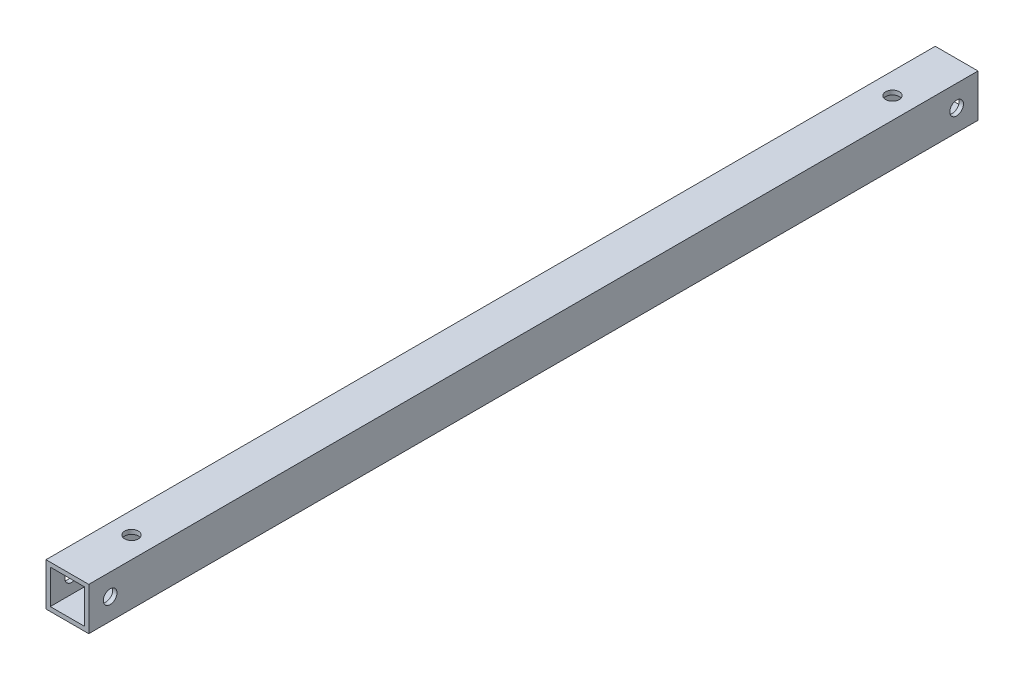
SolidWorks part; units mm, degrees
ref_plane "正面" through (0, 0, 0) normal (0, 0, 1) x (1, 0, 0)
ref_plane "平面" through (0, 0, 0) normal (0, 1, 0) x (1, 0, 0)
ref_plane "右側面" through (0, 0, 0) normal (1, 0, 0) x (0, 0, -1)
sketch "ｽｹｯﾁ1" plane through (0, 0, 0) normal (0, 0, 1) x (1, 0, 0)
  line L0 (-4, 4) -> (-4, -4)
  line L1 (-5, 5) -> (5, 5)
  line L2 (-5, 5) -> (-5, -5)
  line L3 (-5, -5) -> (5, -5)
  line L4 (5, 5) -> (5, -5)
  line L5 (-5, 5) -> (5, -5) construction
  line L6 (-5, -5) -> (5, 5) construction
  line L7 (-4, -4) -> (4, -4)
  line L8 (4, 4) -> (4, -4)
  line L9 (-4, 4) -> (4, 4)
  point P0 (0, 0)
  dimension "D1" = 10
  dimension "D2" = 10
  dimension "D3" = 1
extrude "ﾎﾞｽ - 押し出し1" add sketch "ｽｹｯﾁ1" along normal blind 208
sketch "ｽｹｯﾁ2" plane through (0, 5, 0) normal (0, 1, 0) x (1, 0, 0)
  line L0 (0, -5.5) -> (0, 5.5) construction
  line L1 (5, -208) -> (-5, -208) construction
  line L2 (-5.5, 0) -> (5.5, 0) construction
  circle A0 centre (0, -193) radius 1.6
  circle A1 centre (0, -15) radius 1.6
  dimension "D1" = 3.2
  dimension "D2" = 3.2
  dimension "D3" = 15
  dimension "D4" = 15
extrude "ｶｯﾄ - 押し出し1" cut sketch "ｽｹｯﾁ2" against normal through all
sketch "ｽｹｯﾁ3" plane through (-5, 0, 0) normal (-1, 0, 0) x (0, 0, 1)
  line L0 (5.5, 0) -> (-5.5, 0) construction
  line L1 (208, 5) -> (208, -5) construction
  line L2 (0, -5.5) -> (0, 5.5) construction
  circle A0 centre (203, 0) radius 1.6
  circle A1 centre (5, 0) radius 1.6
  dimension "D1" = 3.2
  dimension "D2" = 3.2
  dimension "D3" = 5
  dimension "D4" = 5
extrude "ｶｯﾄ - 押し出し2" cut sketch "ｽｹｯﾁ3" against normal through all
